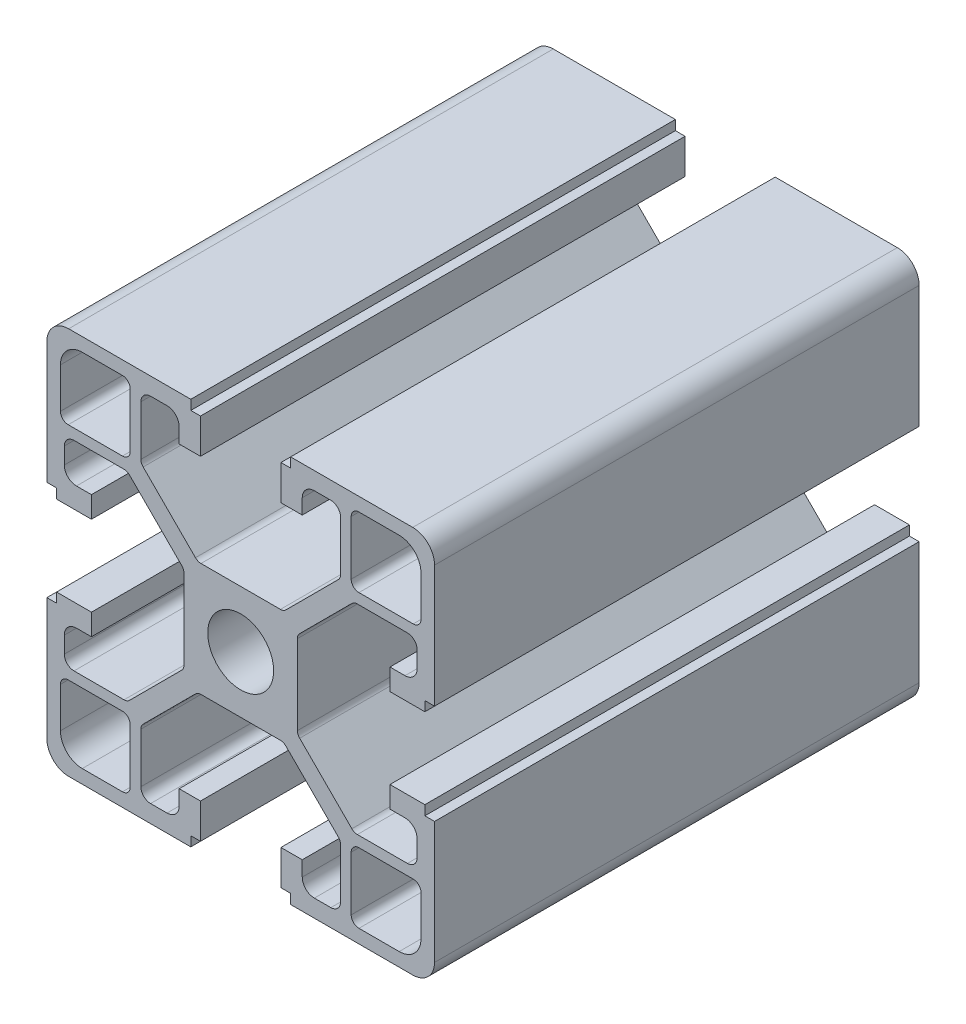
SolidWorks part; units mm, degrees
material "6063-T5"
ref_plane "Front Plane" through (0, 0, 0) normal (0, 0, 1) x (1, 0, 0)
ref_plane "Top Plane" through (0, 0, 0) normal (0, 1, 0) x (1, 0, 0)
ref_plane "Right Plane" through (0, 0, 0) normal (1, 0, 0) x (0, 0, -1)
sketch "Sketch1" plane through (0, 0, 0) normal (0, 0, 1) x (1, 0, 0)
  line L4 (20, 17.75) -> (20, 5.15)
  line L5 (0, -17.7813) -> (0, 18.2) construction
  line L6 (0, 0) -> (38.8613, 0) construction
  line L8 (18.6, 16.35) -> (18.6, 12.2)
  line L10 (11.4, 17.8) -> (11.4, 12.2)
  line L11 (-4.1, 5.85) -> (4.1, 5.85)
  line L14 (5.85, 4.1089) -> (5.85, -4.1089)
  line L17 (12.2, 11.4) -> (17.8, 11.4)
  line L24 (4.15, 19) -> (4.15, 15.4)
  line L25 (4.15, 15.4) -> (6.35, 15.4)
  line L26 (6.35, 15.4) -> (6.35, 16.95)
  line L27 (10.3, 17.2) -> (10.3, 12.0545)
  line L28 (10.0659, 11.489) -> (4.6659, 6.0845)
  line L29 (6.0841, 4.6743) -> (11.4708, 10.0655)
  line L30 (12.0367, 10.3) -> (17.2, 10.3)
  line L31 (18.2, 9.3) -> (18.2, 7.6)
  line L32 (16.95, 6.35) -> (15.4, 6.35)
  line L33 (15.4, 6.35) -> (15.4, 4.15)
  line L34 (15.4, 4.15) -> (19, 4.15)
  line L35 (18.6, 18.6) -> (18.6, -18.6) construction
  line L36 (-18.6, 18.6) -> (18.6, 18.6) construction
  line L37 (-20, 20) -> (20, 20) construction
  line L38 (20, 20) -> (20, -20) construction
  line L40 (7.6, 18.2) -> (9.3, 18.2)
  line L42 (4.15, 19) -> (5.15, 19)
  line L43 (5.15, 19) -> (5.15, 20)
  line L56 (-18.6, 18.6) -> (-18.6, -18.6) construction
  line L57 (-20, 20) -> (-20, -20) construction
  line L60 (5.15, 20) -> (17.75, 20)
  line L91 (-18.6, -18.6) -> (18.6, -18.6) construction
  line L92 (-20, -20) -> (20, -20) construction
  line L93 (12.2, 18.6) -> (16.35, 18.6)
  line L94 (17.9399, 17.9421) -> (20, 20) construction
  line L95 (0, 0) -> (11.4, 11.4094) construction
  line L101 (19, 4.15) -> (19, 5.15)
  line L102 (19, 5.15) -> (20, 5.15)
  line L104 (-5.85, 4.1089) -> (-5.85, -4.1089)
  line L105 (-19, 5.15) -> (-20, 5.15)
  line L106 (-19, 4.15) -> (-19, 5.15)
  line L107 (-12.2, 18.6) -> (-16.35, 18.6)
  line L108 (-5.15, 20) -> (-17.75, 20)
  line L109 (-5.15, 19) -> (-5.15, 20)
  line L110 (-4.15, 19) -> (-5.15, 19)
  line L111 (-7.6, 18.2) -> (-9.3, 18.2)
  line L112 (-15.4, 4.15) -> (-19, 4.15)
  line L113 (-15.4, 6.35) -> (-15.4, 4.15)
  line L114 (-16.95, 6.35) -> (-15.4, 6.35)
  line L115 (-18.2, 9.3) -> (-18.2, 7.6)
  line L116 (-12.0367, 10.3) -> (-17.2, 10.3)
  line L117 (-6.0841, 4.6743) -> (-11.4708, 10.0655)
  line L118 (-10.0659, 11.489) -> (-4.6659, 6.0845)
  line L119 (-10.3, 17.2) -> (-10.3, 12.0545)
  line L120 (-6.35, 15.4) -> (-6.35, 16.95)
  line L121 (-4.15, 15.4) -> (-6.35, 15.4)
  line L122 (-4.15, 19) -> (-4.15, 15.4)
  line L123 (-12.2, 11.4) -> (-17.8, 11.4)
  line L124 (-11.4, 17.8) -> (-11.4, 12.2)
  line L125 (-18.6, 16.35) -> (-18.6, 12.2)
  line L126 (-20, 17.75) -> (-20, 5.15)
  line L127 (-20, -17.75) -> (-20, -5.15)
  line L128 (-18.6, -16.35) -> (-18.6, -12.2)
  line L129 (-11.4, -17.8) -> (-11.4, -12.2)
  line L130 (-12.2, -11.4) -> (-17.8, -11.4)
  line L131 (-4.15, -19) -> (-4.15, -15.4)
  line L132 (-4.15, -15.4) -> (-6.35, -15.4)
  line L133 (-6.35, -15.4) -> (-6.35, -16.95)
  line L134 (-10.3, -17.2) -> (-10.3, -12.0545)
  line L135 (-10.0659, -11.489) -> (-4.6659, -6.0845)
  line L136 (-6.0841, -4.6743) -> (-11.4708, -10.0655)
  line L137 (-12.0367, -10.3) -> (-17.2, -10.3)
  line L138 (-18.2, -9.3) -> (-18.2, -7.6)
  line L139 (-16.95, -6.35) -> (-15.4, -6.35)
  line L140 (-15.4, -6.35) -> (-15.4, -4.15)
  line L141 (-15.4, -4.15) -> (-19, -4.15)
  line L142 (-7.6, -18.2) -> (-9.3, -18.2)
  line L143 (-4.15, -19) -> (-5.15, -19)
  line L144 (-5.15, -19) -> (-5.15, -20)
  line L145 (-5.15, -20) -> (-17.75, -20)
  line L146 (-12.2, -18.6) -> (-16.35, -18.6)
  line L147 (-19, -4.15) -> (-19, -5.15)
  line L148 (-19, -5.15) -> (-20, -5.15)
  line L149 (19, -5.15) -> (20, -5.15)
  line L150 (19, -4.15) -> (19, -5.15)
  line L151 (12.2, -18.6) -> (16.35, -18.6)
  line L152 (5.15, -20) -> (17.75, -20)
  line L153 (5.15, -19) -> (5.15, -20)
  line L154 (4.15, -19) -> (5.15, -19)
  line L155 (7.6, -18.2) -> (9.3, -18.2)
  line L156 (15.4, -4.15) -> (19, -4.15)
  line L157 (15.4, -6.35) -> (15.4, -4.15)
  line L158 (16.95, -6.35) -> (15.4, -6.35)
  line L159 (18.2, -9.3) -> (18.2, -7.6)
  line L160 (12.0367, -10.3) -> (17.2, -10.3)
  line L161 (6.0841, -4.6743) -> (11.4708, -10.0655)
  line L162 (10.0659, -11.489) -> (4.6659, -6.0845)
  line L163 (10.3, -17.2) -> (10.3, -12.0545)
  line L164 (6.35, -15.4) -> (6.35, -16.95)
  line L165 (4.15, -15.4) -> (6.35, -15.4)
  line L166 (4.15, -19) -> (4.15, -15.4)
  line L167 (12.2, -11.4) -> (17.8, -11.4)
  line L168 (-4.1, -5.85) -> (4.1, -5.85)
  line L169 (11.4, -17.8) -> (11.4, -12.2)
  line L170 (18.6, -16.35) -> (18.6, -12.2)
  line L171 (20, -17.75) -> (20, -5.15)
  circle A0 centre (0, 0) radius 3.4
  arc A7 (16.35, 18.6) -> (18.6, 16.35) centre (16.35, 16.35) cw
  arc A8 (20, 17.75) -> (17.75, 20) centre (17.75, 17.75) ccw
  arc A9 (6.35, 16.95) -> (7.6, 18.2) centre (7.6, 16.95) cw
  arc A10 (18.2, 7.6) -> (16.95, 6.35) centre (16.95, 7.6) cw
  arc A11 (17.2, 10.3) -> (18.2, 9.3) centre (17.2, 9.3) cw
  arc A12 (9.3, 18.2) -> (10.3, 17.2) centre (9.3, 17.2) cw
  arc A13 (4.6659, 6.0845) -> (4.1, 5.85) centre (4.1, 6.65) cw
  arc A14 (6.0841, 4.6743) -> (5.85, 4.1089) centre (6.65, 4.1089) ccw
  arc A15 (17.8, 11.4) -> (18.6, 12.2) centre (17.8, 12.2) ccw
  arc A16 (12.2, 18.6) -> (11.4, 17.8) centre (12.2, 17.8) ccw
  arc A17 (11.4, 12.2) -> (12.2, 11.4) centre (12.2, 12.2) ccw
  arc A18 (11.4708, 10.0655) -> (12.0367, 10.3) centre (12.0367, 9.5) cw
  arc A19 (10.3, 12.0545) -> (10.0659, 11.489) centre (9.5, 12.0545) cw
  arc A20 (-10.3, 12.0545) -> (-10.0659, 11.489) centre (-9.5, 12.0545) ccw
  arc A21 (-11.4708, 10.0655) -> (-12.0367, 10.3) centre (-12.0367, 9.5) ccw
  arc A22 (-11.4, 12.2) -> (-12.2, 11.4) centre (-12.2, 12.2) cw
  arc A23 (-12.2, 18.6) -> (-11.4, 17.8) centre (-12.2, 17.8) cw
  arc A24 (-17.8, 11.4) -> (-18.6, 12.2) centre (-17.8, 12.2) cw
  arc A25 (-6.0841, 4.6743) -> (-5.85, 4.1089) centre (-6.65, 4.1089) cw
  arc A26 (-4.6659, 6.0845) -> (-4.1, 5.85) centre (-4.1, 6.65) ccw
  arc A27 (-9.3, 18.2) -> (-10.3, 17.2) centre (-9.3, 17.2) ccw
  arc A28 (-17.2, 10.3) -> (-18.2, 9.3) centre (-17.2, 9.3) ccw
  arc A29 (-18.2, 7.6) -> (-16.95, 6.35) centre (-16.95, 7.6) ccw
  arc A30 (-6.35, 16.95) -> (-7.6, 18.2) centre (-7.6, 16.95) ccw
  arc A31 (-20, 17.75) -> (-17.75, 20) centre (-17.75, 17.75) cw
  arc A32 (-16.35, 18.6) -> (-18.6, 16.35) centre (-16.35, 16.35) ccw
  arc A33 (-16.35, -18.6) -> (-18.6, -16.35) centre (-16.35, -16.35) cw
  arc A34 (-20, -17.75) -> (-17.75, -20) centre (-17.75, -17.75) ccw
  arc A35 (-6.35, -16.95) -> (-7.6, -18.2) centre (-7.6, -16.95) cw
  arc A36 (-18.2, -7.6) -> (-16.95, -6.35) centre (-16.95, -7.6) cw
  arc A37 (-17.2, -10.3) -> (-18.2, -9.3) centre (-17.2, -9.3) cw
  arc A38 (-9.3, -18.2) -> (-10.3, -17.2) centre (-9.3, -17.2) cw
  arc A39 (-4.6659, -6.0845) -> (-4.1, -5.85) centre (-4.1, -6.65) cw
  arc A40 (-6.0841, -4.6743) -> (-5.85, -4.1089) centre (-6.65, -4.1089) ccw
  arc A41 (-17.8, -11.4) -> (-18.6, -12.2) centre (-17.8, -12.2) ccw
  arc A42 (-12.2, -18.6) -> (-11.4, -17.8) centre (-12.2, -17.8) ccw
  arc A43 (-11.4, -12.2) -> (-12.2, -11.4) centre (-12.2, -12.2) ccw
  arc A44 (-11.4708, -10.0655) -> (-12.0367, -10.3) centre (-12.0367, -9.5) cw
  arc A45 (-10.3, -12.0545) -> (-10.0659, -11.489) centre (-9.5, -12.0545) cw
  arc A46 (10.3, -12.0545) -> (10.0659, -11.489) centre (9.5, -12.0545) ccw
  arc A47 (11.4708, -10.0655) -> (12.0367, -10.3) centre (12.0367, -9.5) ccw
  arc A48 (11.4, -12.2) -> (12.2, -11.4) centre (12.2, -12.2) cw
  arc A49 (12.2, -18.6) -> (11.4, -17.8) centre (12.2, -17.8) cw
  arc A50 (17.8, -11.4) -> (18.6, -12.2) centre (17.8, -12.2) cw
  arc A51 (6.0841, -4.6743) -> (5.85, -4.1089) centre (6.65, -4.1089) cw
  arc A52 (4.6659, -6.0845) -> (4.1, -5.85) centre (4.1, -6.65) ccw
  arc A53 (9.3, -18.2) -> (10.3, -17.2) centre (9.3, -17.2) ccw
  arc A54 (17.2, -10.3) -> (18.2, -9.3) centre (17.2, -9.3) ccw
  arc A55 (18.2, -7.6) -> (16.95, -6.35) centre (16.95, -7.6) ccw
  arc A56 (6.35, -16.95) -> (7.6, -18.2) centre (7.6, -16.95) ccw
  arc A57 (20, -17.75) -> (17.75, -20) centre (17.75, -17.75) cw
  arc A58 (16.35, -18.6) -> (18.6, -16.35) centre (16.35, -16.35) ccw
  point P0 (0, 0)
  point P16 (-5.85, 0)
  point P66 (0, 5.85)
  point P120 (5.85, 0)
  point P218 (0, -5.85)
  dimension "D5" = 6.8
  dimension "D6" = 1.4
  dimension "D15" = 5.85
  dimension "D44" = 2.25
  dimension "D25" = 1.25
  dimension "D26" = 1
  dimension "D27" = 0.8
  dimension "D7" = 1.1
  dimension "D8" = 1.1
  dimension "D9" = 1.8
  dimension "D10" = 2.2
  dimension "D11" = 4.6
  dimension "D12" = 1.8
  dimension "D13" = 2.2
  dimension "D14" = 5.85
  dimension "D16" = 1.4
  dimension "D17" = 4.15
  dimension "D18" = 1
  dimension "D19" = 1
  dimension "D20" = 10.3
  dimension "D21" = 4.15
  dimension "D22" = 2
  dimension "D23" = 45.024
  dimension "D24" = 1
  dimension "D41" = 10.3
  dimension "D60" = 14.15
  dimension "D73" = 1
  dimension "D74" = 1
  dimension "D82" = 14.15
  dimension "D3" = 4.6
extrude "Boss-Extrude1" add sketch "Sketch1" along normal blind 713
sketch "Sketch2" plane through (0, 20, 0) normal (0, 1, 0) x (1, 0, 0)
  line L0 (-20, -713) -> (-20, 0) construction
  line L1 (-20, -600) -> (20, -600)
  line L2 (-20, -600) -> (-20, -713)
  line L3 (-20, -713) -> (20, -713)
  line L4 (20, -600) -> (20, -713)
  dimension "D1" = 113
extrude "Cut-Extrude1" cut sketch "Sketch2" against normal through all
sketch "Sketch3" plane through (0, 20, 0) normal (0, 1, 0) x (1, 0, 0)
  line L0 (20, -600) -> (20, 0) construction
  line L1 (-20, -600) -> (20, -600)
  line L2 (-20, -600) -> (-20, -50)
  line L3 (-20, -50) -> (20, -50)
  line L4 (20, -600) -> (20, -50)
  line L5 (-5.15, 0) -> (-17.75, 0) construction
  dimension "D1" = 50
extrude "Cut-Extrude2" cut sketch "Sketch3" against normal through all
